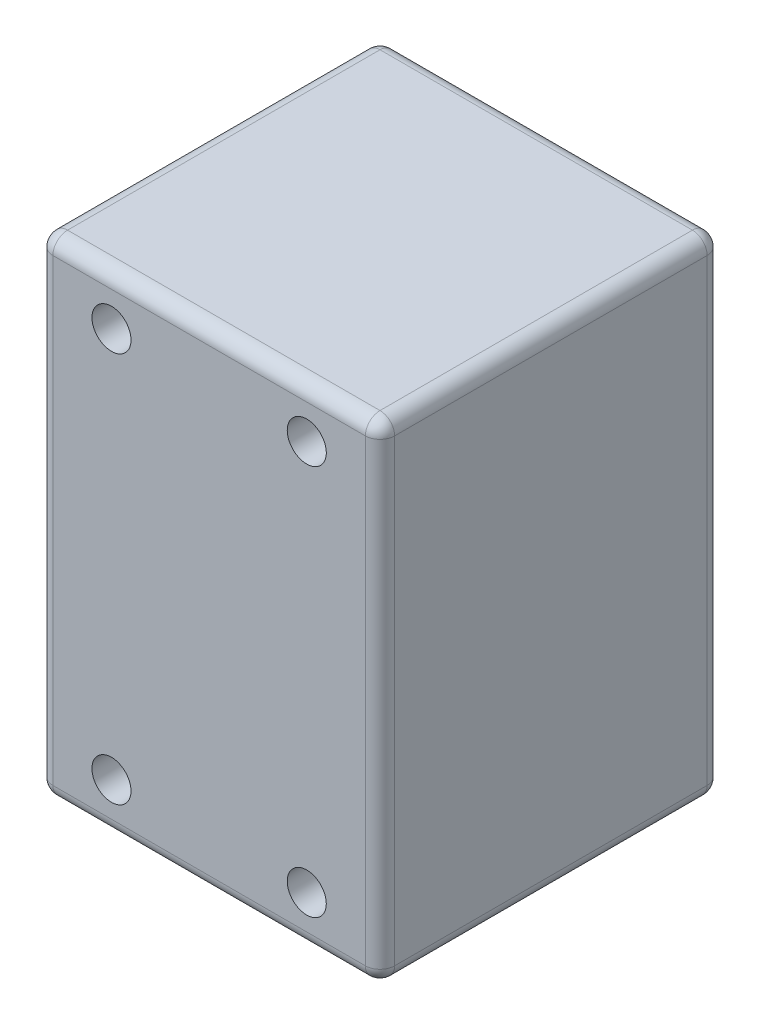
SolidWorks part; units mm, degrees
ref_plane "Front Plane" through (0, 0, 0) normal (0, 0, 1) x (1, 0, 0)
ref_plane "Top Plane" through (0, 0, 0) normal (0, 1, 0) x (1, 0, 0)
ref_plane "Right Plane" through (0, 0, 0) normal (1, 0, 0) x (0, 0, -1)
sketch "Sketch1" plane through (0, 0, 0) normal (0, 0, 1) x (1, 0, 0)
  line L1 (-35, -50) -> (35, -50)
  line L2 (-35, -50) -> (-35, 50)
  line L3 (-35, 50) -> (35, 50)
  line L4 (35, -50) -> (35, 50)
  line L5 (-35, -50) -> (35, 50) construction
  line L6 (-35, 50) -> (35, -50) construction
  point P0 (0, 0)
  dimension "D1" = 100
  dimension "D2" = 70
extrude "Boss-Extrude1" add sketch "Sketch1" along normal blind 70
sketch "Sketch2" plane through (0, 0, 70) normal (0, 0, 1) x (1, 0, 0)
  line L0 (-35, 0) -> (35, 0) construction
  line L1 (-35, 50) -> (-35, -50) construction
  line L2 (35, -50) -> (35, 50) construction
  line L3 (0, 50) -> (0, -50) construction
  line L4 (35, 50) -> (-35, 50) construction
  line L5 (-35, -50) -> (35, -50) construction
  circle A0 centre (-20, 40) radius 4
  circle A1 centre (-20, -40) radius 4
  circle A2 centre (20, -40) radius 4
  circle A3 centre (20, 40) radius 4
  dimension "D1" = 8
  dimension "D3" = 40
  dimension "D2" = 20
extrude "Cut-Extrude1" cut sketch "Sketch2" against normal through all
fillet "Fillet1" radius 3 12 edges at (35, 0, 0) (-35, 0, 0) (0, -50, 0) (-35, -50, 35) (35, -50, 35) (0, -50, 70) (-35, 0, 70) (35, 0, 70) (-35, 50, 35) (0, 50, 0) (35, 50, 35) (0, 50, 70)
equation "\"width\"= 0.07m"
equation "\"height\"= 0.1m"
equation "\"Thick\"= 0.07m"
